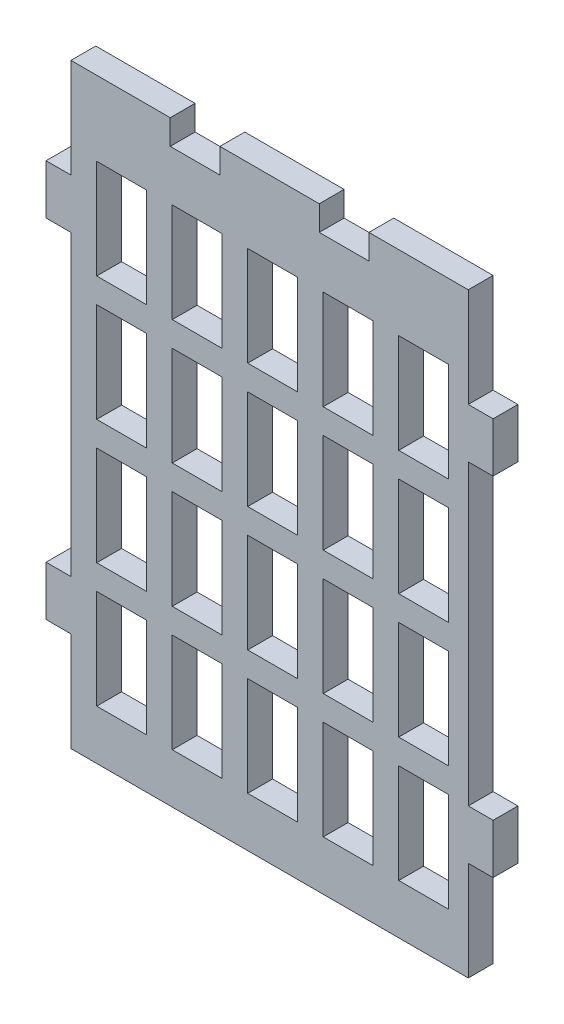
SolidWorks part; units mm, degrees
ref_plane "Front Plane" through (0, 0, 0) normal (0, 0, 1) x (1, 0, 0)
ref_plane "Top Plane" through (0, 0, 0) normal (0, 1, 0) x (1, 0, 0)
ref_plane "Right Plane" through (0, 0, 0) normal (1, 0, 0) x (0, 0, -1)
sketch "Sketch1" plane through (0, 0, 0) normal (0, 0, 1) x (1, 0, 0)
  line L0 (19.05, 0) -> (31.75, 0)
  line L1 (0, 0) -> (12.7, 0)
  line L2 (0, 0) -> (0, -12.7)
  line L3 (0, -76.2) -> (12.7, -76.2)
  line L4 (50.8, -19.05) -> (50.8, -57.15)
  line L5 (38.1, 0) -> (50.8, 0)
  line L6 (12.7, 0) -> (12.7, -3.175)
  line L7 (12.7, -3.175) -> (19.05, -3.175)
  line L8 (19.05, 0) -> (19.05, -3.175)
  line L9 (0, -19.05) -> (0, -57.15)
  line L10 (31.75, 0) -> (31.75, -3.175)
  line L11 (31.75, -3.175) -> (38.1, -3.175)
  line L12 (38.1, 0) -> (38.1, -3.175)
  line L13 (50.8, -12.7) -> (53.975, -12.7)
  line L14 (50.8, -63.5) -> (50.8, -76.2)
  line L15 (50.8, -19.05) -> (53.975, -19.05)
  line L16 (53.975, -12.7) -> (53.975, -19.05)
  line L17 (50.8, -57.15) -> (53.975, -57.15)
  line L18 (38.1, -76.2) -> (50.8, -76.2)
  line L19 (50.8, -63.5) -> (53.975, -63.5)
  line L20 (53.975, -57.15) -> (53.975, -63.5)
  line L21 (12.7, -76.2) -> (38.1, -76.2)
  line L25 (0, -63.5) -> (0, -76.2)
  line L29 (0, -63.5) -> (-3.175, -63.5)
  line L31 (0, -57.15) -> (-3.175, -57.15)
  line L32 (-3.175, -63.5) -> (-3.175, -57.15)
  line L33 (0, -19.05) -> (-3.175, -19.05)
  line L34 (50.8, 0) -> (50.8, -12.7)
  line L35 (0, -12.7) -> (-3.175, -12.7)
  line L36 (-3.175, -19.05) -> (-3.175, -12.7)
  dimension "D3" = 12.7
  dimension "D4" = 6.35
  dimension "D5" = 3.175
  dimension "D6" = 6.35
  dimension "D7" = 3.175
  dimension "D8" = 12.7
  dimension "D9" = 76.2
  dimension "D10" = 6.35
  dimension "D11" = 3.175
  dimension "D12" = 3.175
  dimension "D13" = 6.35
  dimension "D14" = 12.7
  dimension "D15" = 50.8
  dimension "D21" = 3.175
  dimension "D22" = 6.35
  dimension "D23" = 12.7
  dimension "D24" = 12.7
  dimension "D25" = 6.35
  dimension "D26" = 3.175
  dimension "D27" = 3.175
  dimension "D29" = 3.175
  dimension "D30" = 12.7
extrude "Boss-Extrude1" add sketch "Sketch1" along normal blind 3.175
sketch "Sketch2" plane through (0, 0, 3.175) normal (0, 0, 1) x (1, 0, 0)
  line L0 (12.7, -3.175) -> (19.05, -3.175) construction
  line L1 (3.302, -9.525) -> (9.6473, -9.525)
  line L2 (3.302, -9.525) -> (3.302, -22.225)
  line L3 (3.302, -22.225) -> (9.6473, -22.225)
  line L4 (9.6473, -9.525) -> (9.6473, -22.225)
  line L5 (3.302, -9.525) -> (9.6473, -22.225) construction
  line L6 (3.302, -22.225) -> (9.6473, -9.525) construction
  line L7 (0, -19.05) -> (0, -57.15) construction
  point P0 (6.4747, -15.875)
  dimension "D1" = 6.35
  dimension "D2" = 12.7
  dimension "D3" = 6.3453
  dimension "D4" = 3.302
extrude "Cut-Extrude1" cut sketch "Sketch2" against normal blind 5.08
pattern_linear "LPattern1" count 5 spacing 9.652 along (1, 0, 0) count 4 spacing 15.875 along (0, -1, 0) of "Cut-Extrude1"
